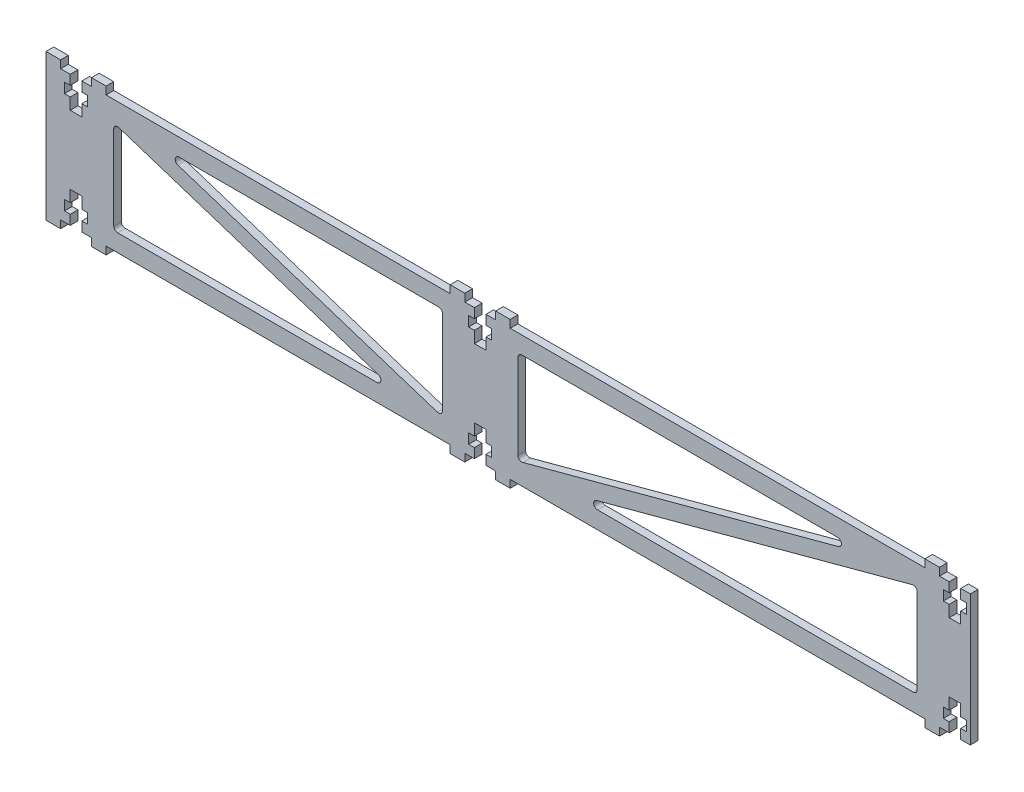
SolidWorks part; units mm, degrees
ref_plane "前视基准面" through (0, 0, 0) normal (0, 0, 1) x (1, 0, 0)
ref_plane "上视基准面" through (0, 0, 0) normal (0, 1, 0) x (1, 0, 0)
ref_plane "右视基准面" through (0, 0, 0) normal (1, 0, 0) x (0, 0, -1)
sketch "草图2" plane through (0, 0, 0) normal (0, 0, 1) x (1, 0, 0)
  line L12 (-23, -1.6) -> (-23, -19.4) construction
  line L29 (-15.2, 6.5) -> (74.2, 6.5)
  line L33 (-27, 8.5) -> (-30.8, 8.5)
  line L34 (-27, 6.5) -> (-24.5, 6.5)
  line L35 (-21.5, 6.5) -> (-19, 6.5)
  line L36 (-19, 8.5) -> (-15.2, 8.5)
  line L37 (-27, 8.5) -> (-27, 6.5)
  line L38 (-19, 8.5) -> (-19, 6.5)
  line L39 (-26, 4) -> (-26, 1.4)
  line L40 (-26, 1.4) -> (-24.5, 1.4)
  line L41 (-24.5, 1.4) -> (-24.5, -1.6)
  line L42 (-21.5, 1.4) -> (-21.5, -1.6)
  line L43 (-20, 1.4) -> (-21.5, 1.4)
  line L44 (-20, 4) -> (-20, 1.4)
  line L45 (-24.5, 4) -> (-26, 4)
  line L46 (-24.5, -1.6) -> (-21.5, -1.6)
  line L47 (-21.5, 4) -> (-20, 4)
  line L48 (-24.5, 4) -> (-24.5, 6.5)
  line L49 (-21.5, 4) -> (-21.5, 6.5)
  line L60 (-21.5, -25) -> (-21.5, -27.5)
  line L70 (-24.5, -25) -> (-24.5, -27.5)
  line L99 (-21.5, -25) -> (-20, -25)
  line L100 (-24.5, -19.4) -> (-21.5, -19.4)
  line L101 (-24.5, -25) -> (-26, -25)
  line L102 (-20, -25) -> (-20, -22.4)
  line L103 (-20, -22.4) -> (-21.5, -22.4)
  line L104 (-21.5, -22.4) -> (-21.5, -19.4)
  line L105 (-24.5, -22.4) -> (-24.5, -19.4)
  line L106 (-26, -22.4) -> (-24.5, -22.4)
  line L107 (-26, -25) -> (-26, -22.4)
  line L108 (-19, -29.5) -> (-19, -27.5)
  line L109 (-27, -29.5) -> (-27, -27.5)
  line L110 (-19, -29.5) -> (-15.2, -29.5)
  line L111 (-21.5, -27.5) -> (-19, -27.5)
  line L112 (-27, -27.5) -> (-24.5, -27.5)
  line L113 (-27, -29.5) -> (-30.8, -29.5)
  line L114 (82, -1.6) -> (82, -19.4) construction
  line L115 (78, 8.5) -> (74.2, 8.5)
  line L116 (78, 6.5) -> (80.5, 6.5)
  line L117 (83.5, 6.5) -> (86, 6.5)
  line L118 (86, 8.5) -> (89.8, 8.5)
  line L119 (78, 8.5) -> (78, 6.5)
  line L120 (86, 8.5) -> (86, 6.5)
  line L121 (79, 4) -> (79, 1.4)
  line L122 (79, 1.4) -> (80.5, 1.4)
  line L123 (80.5, 1.4) -> (80.5, -1.6)
  line L124 (83.5, 1.4) -> (83.5, -1.6)
  line L125 (85, 1.4) -> (83.5, 1.4)
  line L126 (85, 4) -> (85, 1.4)
  line L127 (80.5, 4) -> (79, 4)
  line L128 (80.5, -1.6) -> (83.5, -1.6)
  line L129 (83.5, 4) -> (85, 4)
  line L130 (80.5, 4) -> (80.5, 6.5)
  line L131 (83.5, 4) -> (83.5, 6.5)
  line L132 (83.5, -25) -> (83.5, -27.5)
  line L133 (80.5, -25) -> (80.5, -27.5)
  line L134 (83.5, -25) -> (85, -25)
  line L135 (80.5, -19.4) -> (83.5, -19.4)
  line L136 (80.5, -25) -> (79, -25)
  line L137 (85, -25) -> (85, -22.4)
  line L138 (85, -22.4) -> (83.5, -22.4)
  line L139 (83.5, -22.4) -> (83.5, -19.4)
  line L140 (80.5, -22.4) -> (80.5, -19.4)
  line L141 (79, -22.4) -> (80.5, -22.4)
  line L142 (79, -25) -> (79, -22.4)
  line L143 (86, -29.5) -> (86, -27.5)
  line L144 (78, -29.5) -> (78, -27.5)
  line L145 (86, -29.5) -> (89.8, -29.5)
  line L146 (83.5, -27.5) -> (86, -27.5)
  line L147 (78, -27.5) -> (80.5, -27.5)
  line L148 (78, -29.5) -> (74.2, -29.5)
  line L149 (82, -10.5) -> (162, -10.5) construction
  line L185 (-30.8, 8.5) -> (-30.8, -29.5)
  line L187 (-15.2, 8.5) -> (-15.2, 6.5)
  line L188 (-15.2, -29.5) -> (-15.2, -27.5)
  line L189 (74.2, -29.5) -> (74.2, -27.5)
  line L190 (89.8, -29.5) -> (89.8, -27.5)
  line L191 (74.2, 8.5) -> (74.2, 6.5)
  line L192 (89.8, 8.5) -> (89.8, 6.5)
  line L195 (162, -10.5) -> (205.34, -10.5) construction
  line L196 (205.34, -1.6) -> (205.34, -19.4) construction
  line L197 (201.34, 8.5) -> (197.54, 8.5)
  line L198 (201.34, 6.5) -> (203.84, 6.5)
  line L199 (206.84, 6.5) -> (209.34, 6.5)
  line L200 (201.34, 8.5) -> (201.34, 6.5)
  line L201 (209.34, 6.5) -> (209.34, -27.5)
  line L202 (202.34, 4) -> (202.34, 1.4)
  line L203 (202.34, 1.4) -> (203.84, 1.4)
  line L204 (203.84, 1.4) -> (203.84, -1.6)
  line L205 (206.84, 1.4) -> (206.84, -1.6)
  line L206 (208.34, 1.4) -> (206.84, 1.4)
  line L207 (208.34, 4) -> (208.34, 1.4)
  line L208 (203.84, 4) -> (202.34, 4)
  line L209 (203.84, -1.6) -> (206.84, -1.6)
  line L210 (206.84, 4) -> (208.34, 4)
  line L211 (203.84, 4) -> (203.84, 6.5)
  line L212 (206.84, 4) -> (206.84, 6.5)
  line L213 (206.84, -25) -> (206.84, -27.5)
  line L214 (203.84, -25) -> (203.84, -27.5)
  line L215 (206.84, -25) -> (208.34, -25)
  line L216 (203.84, -19.4) -> (206.84, -19.4)
  line L217 (203.84, -25) -> (202.34, -25)
  line L218 (208.34, -25) -> (208.34, -22.4)
  line L219 (208.34, -22.4) -> (206.84, -22.4)
  line L220 (206.84, -22.4) -> (206.84, -19.4)
  line L221 (203.84, -22.4) -> (203.84, -19.4)
  line L222 (202.34, -22.4) -> (203.84, -22.4)
  line L223 (202.34, -25) -> (202.34, -22.4)
  line L225 (201.34, -29.5) -> (201.34, -27.5)
  line L226 (206.84, -27.5) -> (209.34, -27.5)
  line L227 (201.34, -27.5) -> (203.84, -27.5)
  line L228 (201.34, -29.5) -> (197.54, -29.5)
  line L229 (197.54, 8.5) -> (197.54, 6.5)
  line L230 (197.54, -29.5) -> (197.54, -27.5)
  line L231 (205.34, -10.5) -> (206.84, -10.5) construction
  line L238 (74.2, -27.5) -> (-15.2, -27.5)
  line L251 (89.8, 6.5) -> (197.54, 6.5)
  line L253 (89.8, -25) -> (197.54, 4) construction
  line L254 (89.8, 4) -> (197.54, 4) construction
  line L255 (89.8, 4) -> (89.8, -25) construction
  line L256 (89.8, -25) -> (197.54, -25) construction
  line L257 (197.54, 4) -> (197.54, -25) construction
  line L261 (89.8, -27.5) -> (197.54, -27.5)
  line L265 (-15.2, 4) -> (74.2, -25) construction
  line L266 (-15.2, 4) -> (74.2, 4) construction
  line L267 (-15.2, 4) -> (-15.2, -25) construction
  line L271 (-15.2, -25) -> (74.2, -25) construction
  line L272 (74.2, 4) -> (74.2, -25) construction
  line L273 (3.771, 2) -> (71.2, 2)
  line L274 (92.8, 2) -> (174.8523, 2)
  line L275 (93.0599, -22.0514) -> (175.1122, 0.0344)
  line L276 (91.8, 1) -> (91.8, -21.0857)
  line L277 (112.2278, -21.0344) -> (194.2801, 1.0514)
  line L278 (195.54, 0.0857) -> (195.54, -22)
  line L279 (112.4877, -23) -> (194.54, -23)
  line L280 (91.8, 2) -> (91.8, -22.3905) construction
  line L281 (91.8, 2) -> (182.4149, 2) construction
  line L282 (91.8, -22.3905) -> (182.4149, 2) construction
  line L283 (104.9251, -23) -> (195.54, -23) construction
  line L284 (104.9251, -23) -> (195.54, 1.3905) construction
  line L285 (195.54, 1.3905) -> (195.54, -23) construction
  line L286 (72.2, 1) -> (72.2, -20.873)
  line L287 (3.4624, 0.0488) -> (70.8914, -21.8242)
  line L288 (-13.2, -0.127) -> (-13.2, -22)
  line L289 (-12.2, -23) -> (55.229, -23)
  line L290 (-11.8914, 0.8242) -> (55.5376, -21.0488)
  line L291 (72.2, 2) -> (72.2, -22.2486) construction
  line L292 (-2.5527, 2) -> (72.2, 2) construction
  line L293 (-2.5527, 2) -> (72.2, -22.2486) construction
  line L294 (-13.2, -23) -> (61.5527, -23) construction
  line L295 (-13.2, 1.2486) -> (61.5527, -23) construction
  line L296 (-13.2, 1.2486) -> (-13.2, -23) construction
  arc A32 (91.8, 1) -> (92.8, 2) centre (92.8, 1) cw
  arc A33 (93.0599, -22.0514) -> (91.8, -21.0857) centre (92.8, -21.0857) cw
  arc A34 (175.1122, 0.0344) -> (174.8523, 2) centre (174.8523, 1) ccw
  arc A35 (112.4877, -23) -> (112.2278, -21.0344) centre (112.4877, -22) cw
  arc A36 (195.54, 0.0857) -> (194.2801, 1.0514) centre (194.54, 0.0857) ccw
  arc A37 (195.54, -22) -> (194.54, -23) centre (194.54, -22) cw
  arc A38 (72.2, 1) -> (71.2, 2) centre (71.2, 1) ccw
  arc A39 (70.8914, -21.8242) -> (72.2, -20.873) centre (71.2, -20.873) ccw
  arc A40 (3.4624, 0.0488) -> (3.771, 2) centre (3.771, 1) cw
  arc A41 (55.229, -23) -> (55.5376, -21.0488) centre (55.229, -22) ccw
  arc A42 (-12.2, -23) -> (-13.2, -22) centre (-12.2, -22) cw
  arc A43 (-13.2, -0.127) -> (-11.8914, 0.8242) centre (-12.2, -0.127) cw
  dimension "D3" = 2
  dimension "D4" = 1
  dimension "D10" = 2
  dimension "D11" = 1
  dimension "D12" = 1
  dimension "D14" = 1
  dimension "D15" = 1
  dimension "D16" = 1
  dimension "D13" = 1
  dimension "D2" = 2
  dimension "D9" = 2
extrude "凸台-拉伸1" add sketch "草图2" along normal blind 2
sketch "草图3" plane through (0, 6.5, 0) normal (0, 1, 0) x (1, 0, 0)
  line L0 (80.5, -1) -> (83.5, -1) construction
  line L1 (80.5, -2) -> (80.5, 0) construction
  line L2 (83.5, -2) -> (83.5, 0) construction
  circle A0 centre (82, -1) radius 1.5
